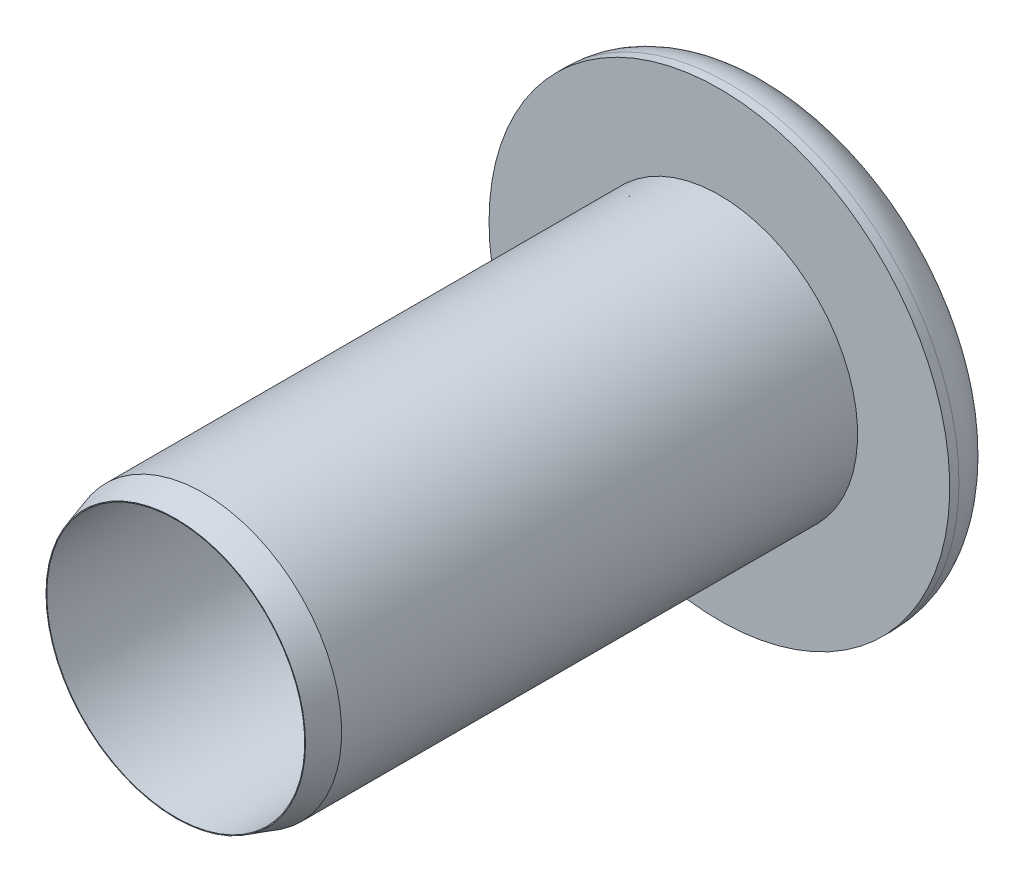
SolidWorks part; units mm, degrees
ref_plane "Plano frontal" through (0, 0, 0) normal (0, 0, 1) x (1, 0, 0)
ref_plane "Plano superior" through (0, 0, 0) normal (0, 1, 0) x (1, 0, 0)
ref_plane "Plano direito" through (0, 0, 0) normal (1, 0, 0) x (0, 0, -1)
sketch "Esboço1" plane through (0, 0, 0) normal (0, 0, 1) x (1, 0, 0)
  circle A0 centre (0, 0) radius 1.5
  circle A1 centre (0, 0) radius 1.4
  dimension "D1" = 3
  dimension "D2" = 2.8
extrude "Ressalto-extrusão1" add sketch "Esboço1" along normal blind 6.5
sketch "Esboço2" plane through (0, 0, 0) normal (0, 0, -1) x (-1, 0, 0)
  circle A0 centre (0, 0) radius 2.5
  circle A1 centre (0, 0) radius 1.5
  dimension "D1" = 5
extrude "Ressalto-extrusão2" add sketch "Esboço2" against normal blind 0.6
fillet "Filete1" radius 0.5 2 edges at (1.4, 0, 0) (-2.5, 0, 0)
chamfer "Chanfro1" distance 0.3 angle 17 1 edges at (1.5, 0, 6.5)
